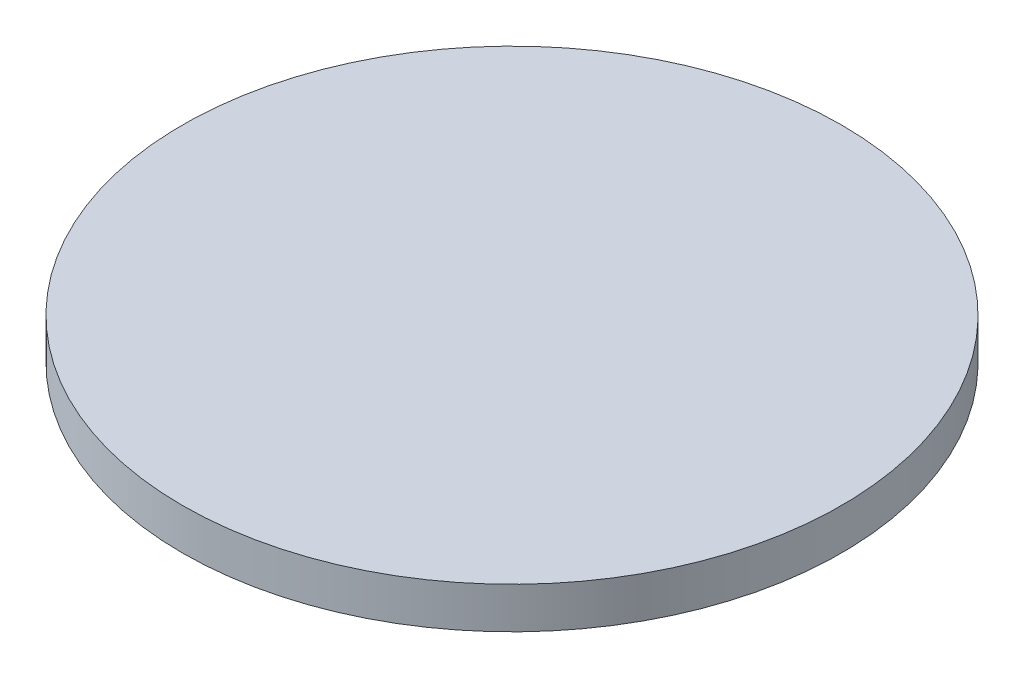
SolidWorks part; units mm, degrees
material "Хромистая нержавеющая сталь"
ref_plane "Спереди" through (0, 0, 0) normal (0, 0, 1) x (1, 0, 0)
ref_plane "Сверху" through (0, 0, 0) normal (0, 1, 0) x (1, 0, 0)
ref_plane "Справа" through (0, 0, 0) normal (1, 0, 0) x (0, 0, -1)
sketch "Эскиз1" plane through (0, 0, 0) normal (0, 1, 0) x (1, 0, 0)
  circle A0 centre (0, 0) radius 8
  dimension "D1" = 16
extrude "База" add sketch "Эскиз1" along normal blind 1
